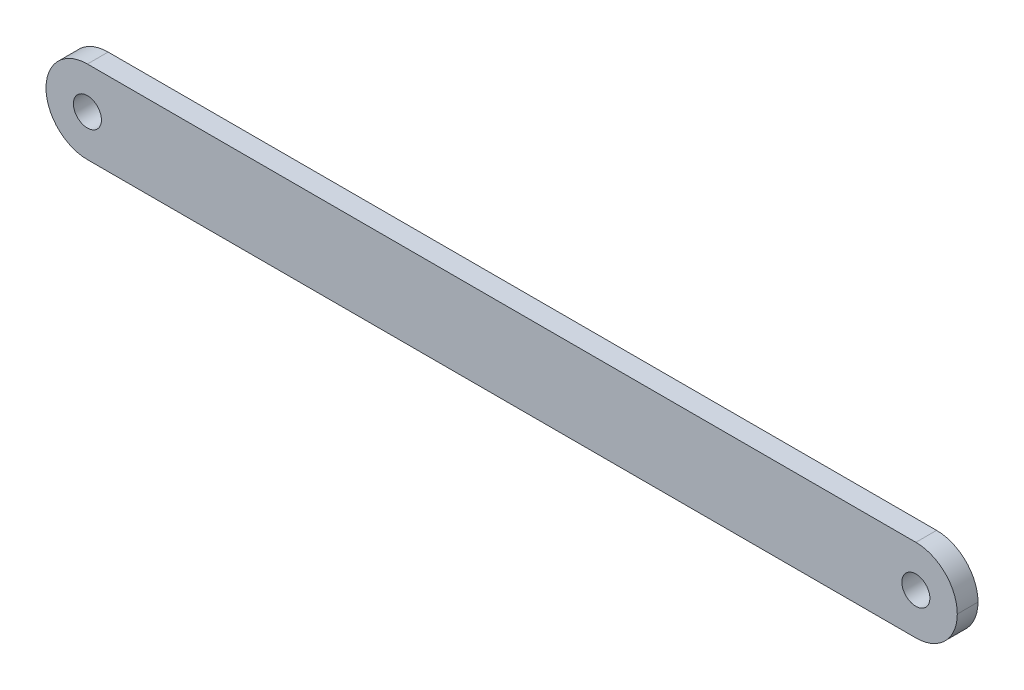
SolidWorks part; units mm, degrees
ref_plane "前视基准面" through (0, 0, 0) normal (0, 0, 1) x (1, 0, 0)
ref_plane "上视基准面" through (0, 0, 0) normal (0, 1, 0) x (1, 0, 0)
ref_plane "右视基准面" through (0, 0, 0) normal (1, 0, 0) x (0, 0, -1)
ref_plane "基准面1" through (0, 0, 3) normal (0, 0, 1) x (1, 0, 0)
sketch "草图1" plane through (0, 0, 3) normal (0, 0, 1) x (1, 0, 0)
  line L0 (55.8602, 7.999) -> (-24.1383, 7.999)
  line L1 (-24.1383, 0) -> (55.8602, 0)
  circle A0 centre (55.8597, 3.9995) radius 1.354
  circle A1 centre (-24.1388, 3.9985) radius 1.354
  arc A2 (55.8602, 0) -> (59.8602, 4) centre (55.8602, 4) ccw
  arc A3 (59.8602, 4) -> (55.8602, 7.999) centre (55.8602, 3.999) ccw
  arc A4 (-24.1383, 7.999) -> (-28.1383, 3.999) centre (-24.1383, 3.999) ccw
  arc A5 (-28.1383, 3.999) -> (-24.1383, 0) centre (-24.1383, 4) ccw
extrude "凸台-拉伸1" add sketch "草图1" against normal blind 2
